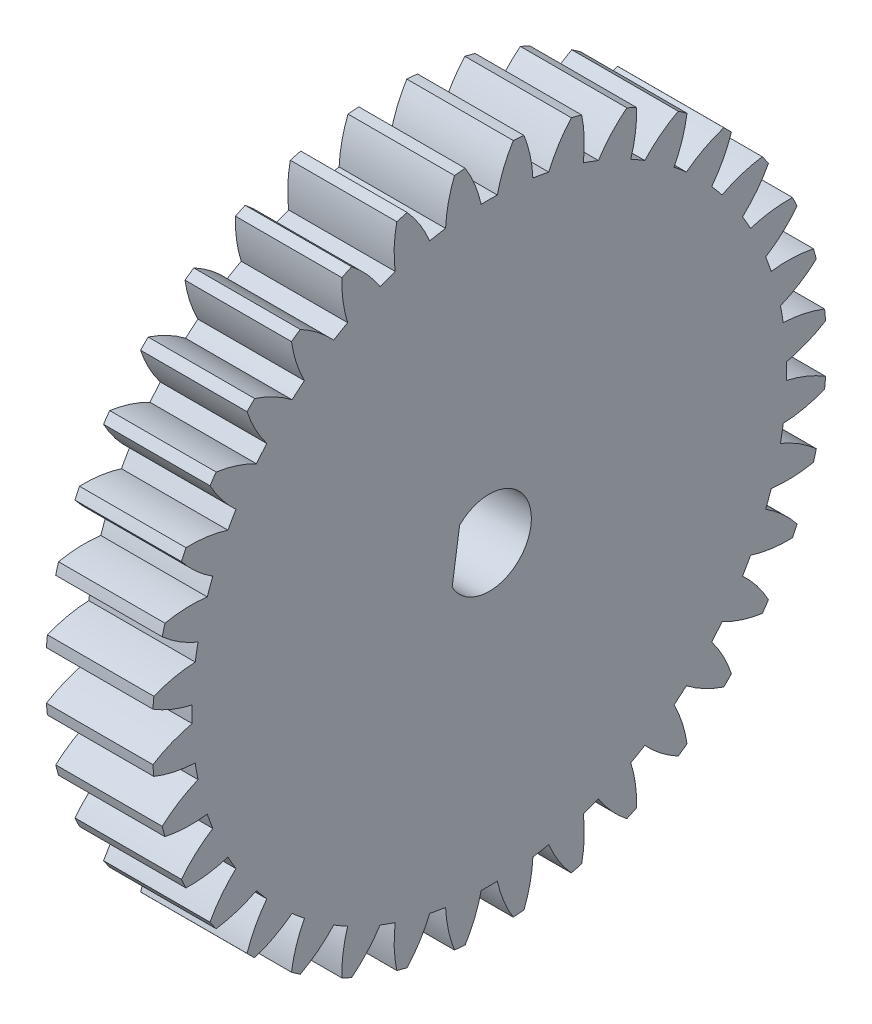
SolidWorks part; units mm, degrees
ref_plane "Plane1" through (0, 0, 0) normal (0, 0, 1) x (1, 0, 0)
ref_plane "Plane2" through (0, 0, 0) normal (0, 1, 0) x (1, 0, 0)
ref_plane "Plane3" through (0, 0, 0) normal (1, 0, 0) x (0, 0, -1)
sketch "HoldingSke" plane through (0, 0, 0) normal (0, 1, 0) x (1, 0, 0)
  line L0 (0, 0) -> (0.809, -0.5878)
  line L1 (-15, 0) -> (100, 0) construction
  line L2 (0, 0) -> (-2.1039, 2.3779)
  line L3 (0, 0) -> (-11.863, 4.5341)
  line L4 (0, 0) -> (6.9867, 5.0761)
  line L5 (0, 0) -> (-46.8476, -17.4728)
  line L6 (0, 0) -> (-4.9738, -3.3558)
  line L7 (-2.1039, 2.3779) -> (8.6586, 51.2059)
  line L8 (-76.2, 54.61) -> (-76.1, 54.61)
  line L9 (-71.009, 38.7566) -> (-53.1078, 45.2721)
  line L10 (-76.2, 71.12) -> (104.1128, 71.12)
  line L11 (0, 0) -> (-6, 0)
  line L12 (-76.2, 101.6) -> (-76.162, 101.6)
  line L13 (24.9733, 27.94) -> (52.9518, 28.4284)
  line L14 (24.9733, 27.94) -> (24.9743, 27.94)
  line L15 (24.9733, 27.94) -> (100.4006, 29.5858)
  line L16 (-63.627, -1) -> (-12.827, -1)
  circle A0 centre (0, 0) radius 0.4
  circle A1 centre (0, 0) radius 16.749
  circle A2 centre (0, 0) radius 37.5
  circle A3 centre (0, 0) radius 0.4
  dimension "MHD" = 33.498
  dimension "Hub_dia" = 75
  dimension "Bore" = 0.8
  dimension "MBD" = 0.8
  dimension "Num_teeth" = 36
  dimension "Pitch" = 1
  dimension "Overall_len" = 50
  dimension "Show_teeth" = 36
  dimension "Thickness" = 6
  dimension "OAL" = 50.0001
  dimension "T_dim" = 0.1
  dimension "Ap" = 20
  dimension "H" = 19.05
  dimension "Pitch_radius" = 180.3128
  dimension "Width" = 6
  dimension "Backlash" = 0.038
  dimension "Addendum_fac" = 1
  dimension "Dedendum_fac" = 1.25
  dimension "Clearance_fac" = 0.25
  dimension "Dedendum_add" = 0.001
  dimension "Module" = 1
sketch "BasProSke" plane through (0, 0, 0) normal (0, 1, 0) x (1, 0, 0)
  line L0 (-10, 0) -> (60, 0) construction
  line L1 (0, 0) -> (0, 19)
  line L2 (0, 0) -> (6, 0)
  line L3 (6, 0) -> (6, 19)
  line L4 (6, 19) -> (0, 19)
  dimension "Thickness" = 6
  dimension "Diameter" = 38
revolve "Base-Revolve" add sketch "BasProSke" angle 360 about L0
sketch "TooCutSke" plane through (0, 0, 0) normal (1, 0, 0) x (0, 0, -1)
  line L1 (0, 0) -> (0, 107) construction
  line L2 (0, 0) -> (-0.8516, 17.9798) construction
  line L3 (0, 0) -> (-3.1351, 35.8344) construction
  line L4 (-0.8516, 17.9798) -> (-1.5676, 17.9172) construction
  arc A0 (0.4547, 16.7428) -> (-0.4547, 16.7428) centre (0, 0) ccw
  arc A1 (1.3689, 18.9761) -> (-1.3689, 18.9761) centre (0, 0) ccw
  circle A2 centre (0, 0) radius 18 construction
  circle A3 centre (0, 0) radius 16.9145 construction
  arc A4 (-0.4547, 16.7428) -> (-1.3689, 18.9761) centre (-7.4808, 15.1702) ccw
  arc A5 (1.3689, 18.9761) -> (0.4547, 16.7428) centre (7.4808, 15.1702) ccw
  dimension "Root_dia" = 33.498
  dimension "Overcut_dia" = 38.0508
  dimension "Pitch_dia" = 36
  dimension "Base_dia" = 33.8289
  dimension "Flank_rad" = 7.2
  dimension "Half_ang" = 5
  dimension "Half_CT" = 0.7186
extrude "ToothCut" cut sketch "TooCutSke" along normal through all
fillet "Breaks" [suppressed] radius 0.02
fillet "RootFillets" [suppressed] radius 0.251
pattern_circular "TeethCuts" count 36 over 360 about axis through (0, 0, 0) along (1, 0, 0) of "ToothCut", "RootFillets", "Breaks"
sketch "HubNeaOneSke" plane through (0, 0, 0) normal (-1, 0, 0) x (0, 0, 1)
  circle A0 centre (0, 0) radius 16.749
  dimension "Diameter" = 33.498
extrude "HubNearOne" [suppressed] add sketch "HubNeaOneSke" along normal blind 44.0001
sketch "HubNeaBotSke" plane through (0, 0, 0) normal (-1, 0, 0) x (0, 0, 1)
  circle A0 centre (0, 0) radius 16.749
  dimension "Diameter" = 33.498
extrude "HubNearBoth" [suppressed] add sketch "HubNeaBotSke" along normal blind 22
ref_plane "FarPln" through (6, 0, 0) normal (1, 0, 0) x (0, 0, -1)
sketch "HubFarSke" plane through (6, 0, 0) normal (1, 0, 0) x (0, 0, -1)
  circle A0 centre (0, 0) radius 16.749
  dimension "Diameter" = 33.498
extrude "HubFar" [suppressed] add sketch "HubFarSke" along normal blind 22
sketch "BorSke" plane through (0, 0, 0) normal (1, 0, 0) x (0, 0, -1)
  line L0 (-2.2004, -1.1866) -> (-1.7553, 1.7802)
  arc A0 (-2.2004, -1.1866) -> (-1.7553, 1.7802) centre (0, 0) ccw
  dimension "D1" = 3
  dimension "D2" = 2.5
extrude "Bore" cut sketch "BorSke" along normal mid plane 100.0001
sketch "KeySke" plane through (0, 0, 0) normal (1, 0, 0) x (0, 0, -1)
  line L0 (-0.05, 0) -> (-0.05, 0.5)
  line L1 (-0.05, 0.5) -> (0.05, 0.5)
  line L2 (0.05, 0.5) -> (0.05, 0)
  line L3 (0, 0) -> (0, 34) construction
  line L4 (-0.05, 0) -> (0.05, 0)
  dimension "Offset" = 0.5
  dimension "Width" = 0.1
extrude "Keyway" [suppressed] cut sketch "KeySke" along normal mid plane 100.0001
pattern_circular "Keyway2" [suppressed] count 2 every 90 about axis through (-10, 0, 0) along (1, 0, 0)
ref_plane "Plane4" through (6, -1.1866, 2.2004) normal (0, -0.8802, -0.4747) x (-1, 0, 0)
sketch "Sketch2" plane through (6, 0, 0) normal (1, 0, 0) x (0, 0, -1)
  line L0 (-2.0904, -1.1273) -> (-1.6675, 1.6912)
  arc A0 (-1.6675, 1.6912) -> (-2.0904, -1.1273) centre (0, 0) cw
  point P5 (0, 0)
  point P8 (0, 0)
ref_plane "Plane5" through (6, 1.7802, 1.7553) normal (0, -0.9889, 0.1484) x (-1, 0, 0)
sketch "Sketch4" plane through (6, 0, 0) normal (1, 0, 0) x (0, 0, -1)
  circle A0 centre (0, 0) radius 6.3694
extrude "Boss-Extrude1" add sketch "Sketch4" against normal blind 6
extrude "Cut-Extrude1" cut sketch "Sketch2" against normal blind 6
equation "' \"Module@HoldingSke\" = 6.35"
equation "' \"Num_teeth@HoldingSke\" = 12"
equation "' \"Ap@HoldingSke\" =  20"
equation "' \"Ap@HoldingSke\" = 20"
equation "' \"Width@HoldingSke\" = 0.5 * 25.4"
equation "' \"Hub_dia@HoldingSke\"= 1 * 25.4"
equation "' \"Hub_dia@HoldingSke\" = 1 * 25.4"
equation "' \"Overall_len@HoldingSke\" = 1.0 * 25.4"
equation "' \"Bore@HoldingSke\" = 0.75 * 25.4"
equation "' \"T_dim@HoldingSke\" = 0.1 * 25.4"
equation "' \"Width@KeySke\" = 0.25 * 25.4"
equation "' \"Show_teeth@HoldingSke\" = 13"
equation "' \"Backlash@HoldingSke\" = 0.009 * 25.4"
equation "' \"Addendum_fac@HoldingSke\" = 1.0"
equation "' \"Dedendum_fac@HoldingSke\" = 1.25"
equation "' \"Dedendum_add@HoldingSke\" = 0.00005 * 25.4"
equation "' \"Clearance_fac@HoldingSke\" = 0.25"
equation "\"Pitch@HoldingSke\" = 1 / \"Module@HoldingSke\""
equation "\"Overcut_dia@TooCutSke\" = (\"Num_teeth@HoldingSke\" + 2 * \"Addendum_fac@HoldingSke\") / \"Pitch@HoldingSke\" + 0.002 * 25.4"
equation "\"Pitch_dia@TooCutSke\" = \"Num_teeth@HoldingSke\" / \"Pitch@HoldingSke\""
equation "\"Base_dia@TooCutSke\" = \"Num_teeth@HoldingSke\" / \"Pitch@HoldingSke\" * cos((\"Ap@HoldingSke\"  * 3.14159265 / 180))"
equation "\"Root_dia@TooCutSke\" = (\"Num_teeth@HoldingSke\" + 2) / \"Pitch@HoldingSke\" - 2 * (\"Addendum_fac@HoldingSke\" + \"Dedendum_fac@HoldingSke\") / \"Pitch@HoldingSke\" - \"Dedendum_add@HoldingSke\" * 2"
equation "\"Half_ang@TooCutSke\" = 180 / \"Num_teeth@HoldingSke\""
equation "\"Half_CT@TooCutSke\" = \"Num_teeth@HoldingSke\" / \"Pitch@HoldingSke\" * sin((3.14159265 / 2 / \"Num_teeth@HoldingSke\")) / 2 - 7 * \"Backlash@HoldingSke\" / 4"
equation "\"Flank_rad@TooCutSke\" = \"Num_teeth@HoldingSke\" / \"Pitch@HoldingSke\" / 5"
equation "\"Radius@RootFillets\" = \"Clearance_fac@HoldingSke\" / \"Pitch@HoldingSke\" + \"Dedendum_add@HoldingSke\""
equation "\"Break_rad@Breaks\" = 0.02 / \"Pitch@HoldingSke\""
equation "\"Thickness@HoldingSke\" = \"Width@HoldingSke\""
equation "\"OAL@HoldingSke\" = \"Thickness@HoldingSke\""
equation "\"MHD@HoldingSke\" = (\"Num_teeth@HoldingSke\" + 2) / \"Pitch@HoldingSke\" - 2 * (\"Addendum_fac@HoldingSke\" + \"Dedendum_fac@HoldingSke\")  / \"Pitch@HoldingSke\" - \"Dedendum_add@HoldingSke\" * 2"
equation "\"MBD@HoldingSke\" = (\"Num_teeth@HoldingSke\" + 2) / \"Pitch@HoldingSke\" - 2 * (\"Addendum_fac@HoldingSke\" + \"Dedendum_fac@HoldingSke\")  / \"Pitch@HoldingSke\" - \"Dedendum_add@HoldingSke\" * 2 - 0.002 * 25.4"
equation "\"MHD@HoldingSke\" = ((sgn( \"MHD@HoldingSke\" - \"Hub_dia@HoldingSke\" )-1)*( \"MHD@HoldingSke\" - \"Hub_dia@HoldingSke\" ))/-2+ \"Hub_dia@HoldingSke\""
equation "\"MBD@HoldingSke\" = ((sgn( \"MBD@HoldingSke\" - \"Bore@HoldingSke\" )-1)*( \"MBD@HoldingSke\" - \"Bore@HoldingSke\" ))/-2+ \"Bore@HoldingSke\""
equation "\"OAL@HoldingSke\" = ((sgn( \"OAL@HoldingSke\" - \"Overall_len@HoldingSke\" )+1)*( \"OAL@HoldingSke\" - \"Overall_len@HoldingSke\" ))/2 + \"Overall_len@HoldingSke\" + 0.000002 * 25.4"
equation "\"Num_teeth@TeethCuts\" = int( \"Show_teeth@HoldingSke\" ) + 1"
equation "\"Num_teeth@TeethCuts\" = ((sgn( \"Num_teeth@TeethCuts\" - \"Num_teeth@HoldingSke\" )-1)*( \"Num_teeth@TeethCuts\" - \"Num_teeth@HoldingSke\" ))/-2+ \"Num_teeth@HoldingSke\""
equation "\"Num_teeth@TeethCuts\" = ((sgn( \"Num_teeth@TeethCuts\" - 2.0)+1)*( \"Num_teeth@TeethCuts\" - 2.0))/2 +2.0"
equation "\"Angle@TeethCuts\" = 360.0 / \"Num_teeth@HoldingSke\""
equation "\"Diameter@BasProSke\" = (\"Num_teeth@HoldingSke\" + 2 * \"Addendum_fac@HoldingSke\") / \"Pitch@HoldingSke\""
equation "\"Thickness@BasProSke\"  = \"Thickness@HoldingSke\""
equation "' \"Fillet_rad@BasProSke\" =  \"Thickness@HoldingSke\" * 0.05"
equation "' \"Fillet_rad@BasProSke\" = \"Thickness@HoldingSke\" * 0.05"
equation "\"MHD@HoldingSke\" = ((sgn( \"MHD@HoldingSke\" - \"Root_dia@TooCutSke\" )-1)*( \"MHD@HoldingSke\" - \"Root_dia@TooCutSke\" ))/-2+ \"Root_dia@TooCutSke\""
equation "\"Diameter@HubNeaOneSke\" = \"MHD@HoldingSke\""
equation "\"Length@HubNearOne\" = \"OAL@HoldingSke\" - \"Thickness@BasProSke\""
equation "\"Diameter@HubNeaBotSke\" = \"MHD@HoldingSke\""
equation "\"Length@HubNearBoth\" = ( \"OAL@HoldingSke\" - \"Thickness@BasProSke\" ) / 2.0"
equation "\"Thickness@FarPln\" = \"Thickness@BasProSke\""
equation "\"Diameter@HubFarSke\" = \"MHD@HoldingSke\""
equation "\"Length@HubFar\" = ( \"OAL@HoldingSke\" - \"Thickness@BasProSke\" ) / 2.0"
equation "\"D1@Bore\" = \"OAL@HoldingSke\" * 2.0"
equation "\"D1@Keyway\" = \"OAL@HoldingSke\" * 2.0"
equation "\"Offset@KeySke\" = \"T_dim@HoldingSke\" + \"MBD@HoldingSke\" / 2.0"
